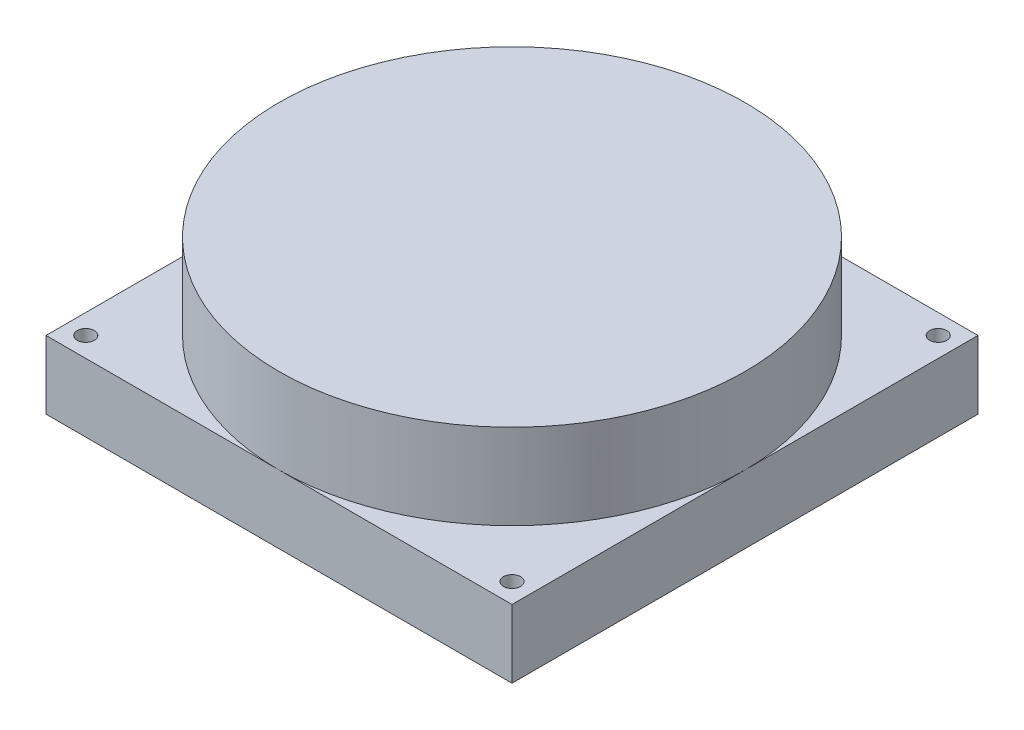
SolidWorks part; units mm, degrees
ref_plane "Front Plane" through (0, 0, 0) normal (0, 0, 1) x (1, 0, 0)
ref_plane "Top Plane" through (0, 0, 0) normal (0, 1, 0) x (1, 0, 0)
ref_plane "Right Plane" through (0, 0, 0) normal (1, 0, 0) x (0, 0, -1)
sketch "Sketch1" plane through (0, 0, 0) normal (0, 1, 0) x (1, 0, 0)
  line L1 (-89.0469, 26.3724) -> (-7.0469, 26.3724)
  line L2 (-89.0469, 26.3724) -> (-89.0469, -55.6276)
  line L3 (-89.0469, -55.6276) -> (-7.0469, -55.6276)
  line L4 (-7.0469, 26.3724) -> (-7.0469, -55.6276)
  dimension "D1" = 82
  dimension "D2" = 82
extrude "Boss-Extrude1" add sketch "Sketch1" along normal blind 12
sketch "Sketch2" plane through (0, 0, 0) normal (0, -1, 0) x (1, 0, 0)
  line L0 (-89.0469, 55.6276) -> (-7.0469, 55.6276) construction
  line L1 (-89.0469, -26.3724) -> (-89.0469, 55.6276) construction
  line L2 (-7.0469, 55.6276) -> (-7.0469, -26.3724) construction
  line L3 (-7.0469, -26.3724) -> (-89.0469, -26.3724) construction
  circle A0 centre (-85.5469, 52.1276) radius 1.5
  circle A1 centre (-10.5469, 52.1276) radius 1.5
  circle A2 centre (-85.5469, -22.8724) radius 1.5
  circle A3 centre (-10.5469, -22.8724) radius 1.5
  dimension "D1" = 3.5
  dimension "D2" = 3.5
  dimension "D3" = 3
  dimension "D4" = 3
  dimension "D6" = 3
  dimension "D7" = 3.5
  dimension "D8" = 3
  dimension "D5" = 3.5
extrude "Cut-Extrude1" cut sketch "Sketch2" against normal through all
sketch "Sketch3" plane through (0, 12, 0) normal (0, 1, 0) x (1, 0, 0)
  line L0 (-7.0469, -55.6276) -> (-7.0469, 26.3724) construction
  line L1 (-89.0469, 26.3724) -> (-89.0469, -55.6276) construction
  line L2 (-89.0469, -55.6276) -> (-7.0469, -55.6276) construction
  circle A0 centre (-48.0469, -14.6276) radius 41
extrude "Boss-Extrude2" add sketch "Sketch3" along normal blind 15
sketch "Sketch4" plane through (0, 0, 0) normal (0, -1, 0) x (1, 0, 0)
  line L0 (-7.0469, -26.3724) -> (-89.0469, -26.3724) construction
  line L1 (-62.0469, 5.6276) -> (-34.0469, 5.6276) construction
  line L2 (-62.0469, 5.6276) -> (-62.0469, 32.6276) construction
  line L3 (-62.0469, 32.6276) -> (-34.0469, 32.6276) construction
  line L4 (-34.0469, 5.6276) -> (-34.0469, 32.6276) construction
  line L5 (-89.0469, 55.6276) -> (-7.0469, 55.6276) construction
  circle A0 centre (-57.0469, 14.8776) radius 1.5
  circle A1 centre (-39.0469, 14.8776) radius 1.5
  point P4 (-48.0469, 5.6276)
  point P7 (-48.0469, -26.3724)
  point P14 (0, 0)
  dimension "D4" = 17.75
  dimension "D5" = 3
  dimension "D6" = 3
  dimension "D7" = 5
  dimension "D8" = 18
  dimension "D1" = 28
  dimension "D2" = 27
  dimension "D3" = 23
extrude "Cut-Extrude2" cut sketch "Sketch4" against normal blind 5
